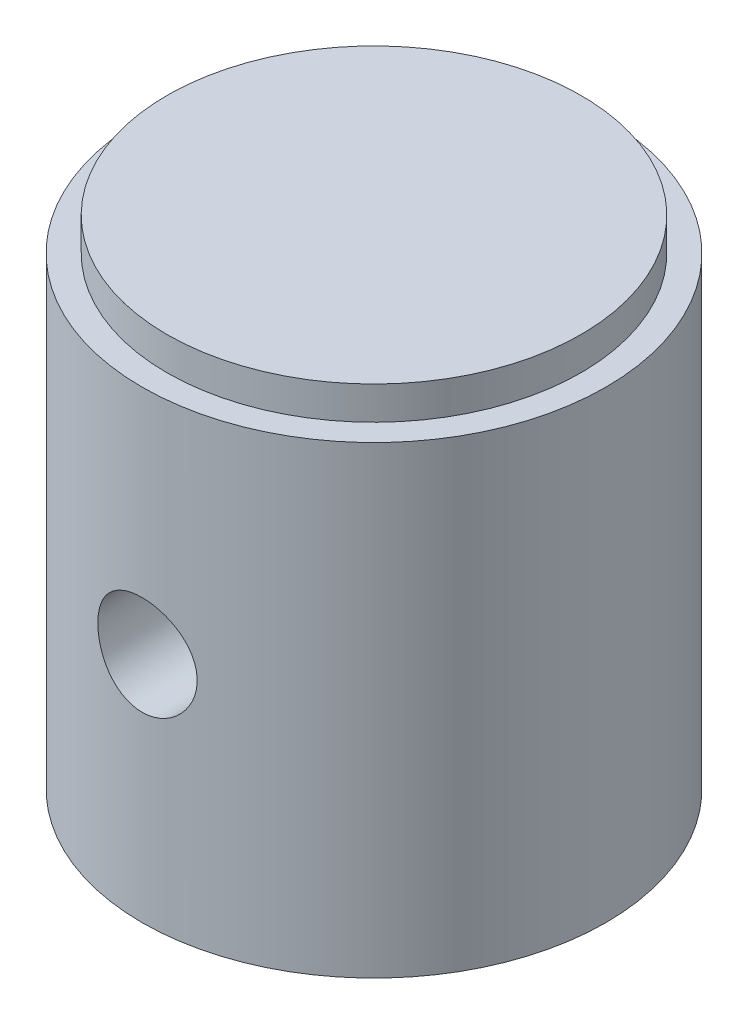
SolidWorks part; units mm, degrees
ref_plane "Front Plane" through (0, 0, 0) normal (0, 0, 1) x (1, 0, 0)
ref_plane "Top Plane" through (0, 0, 0) normal (0, 1, 0) x (1, 0, 0)
ref_plane "Right Plane" through (0, 0, 0) normal (1, 0, 0) x (0, 0, -1)
sketch "Sketch2" plane through (0, 0, 0) normal (0, 0, 1) x (1, 0, 0)
  line L0 (-23, 0) -> (0, 0) construction
  line L1 (0, 19.6875) -> (0, -20.5625) construction
  line L2 (-6.2, -7) -> (-4.75, -3.0162)
  line L3 (-4.75, -3.0162) -> (-4.75, 4)
  line L4 (-4.75, 4) -> (0, 6.8541)
  line L12 (0, 8) -> (-6.25, 8)
  line L13 (-6.25, 8) -> (-6.25, 7)
  line L14 (-6.25, 7) -> (-7, 7)
  line L15 (-7, 7) -> (-7, -7)
  line L16 (-7, -7) -> (-6.2, -7)
  line L17 (0, 8) -> (0, 6.8541)
  point P10 (-5.475, -5.0081)
  dimension "D1" = 7
  dimension "D2" = 6.2
  dimension "D3" = 4.75
  dimension "D4" = 7
  dimension "D5" = 11
  dimension "D6" = 6.25
  dimension "D7" = 1
  dimension "D8" = 20
  dimension "D9" = 15
  dimension "D10" = 59
revolve "Revolve1" add sketch "Sketch2" angle 360 about L1
sketch "Sketch3" plane through (0, 0, 0) normal (0, 0, 1) x (1, 0, 0)
  circle A0 centre (0, 0) radius 1.5
extrude "Cut-Extrude1" cut sketch "Sketch3" against normal through all both and the other way through all
